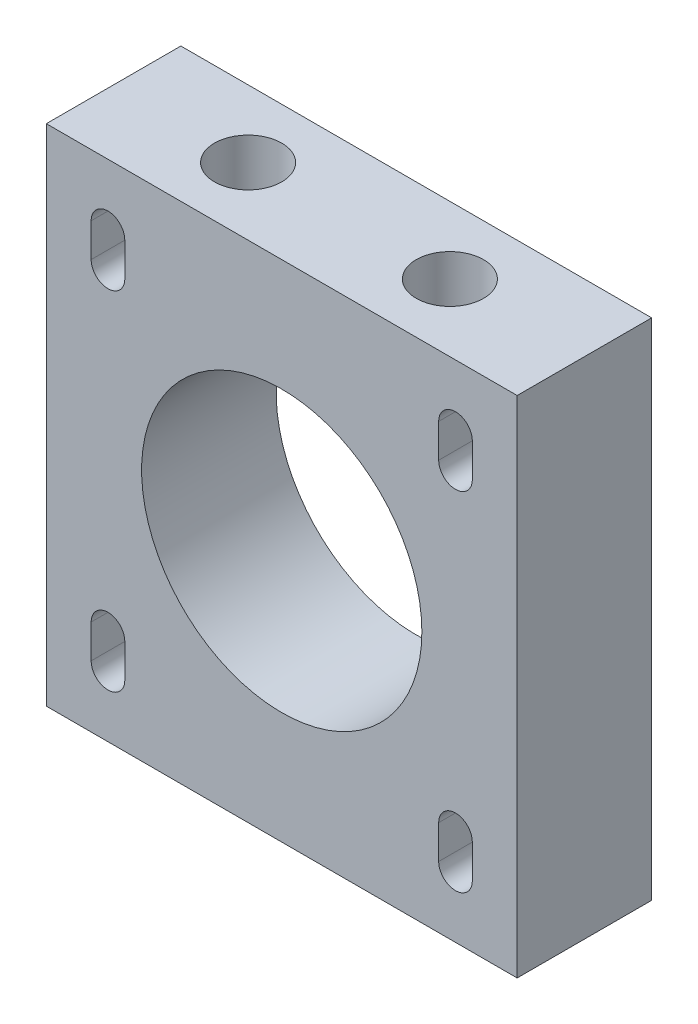
SolidWorks part; units mm, degrees
ref_plane "前视基准面" through (0, 0, 0) normal (0, 0, 1) x (1, 0, 0)
ref_plane "上视基准面" through (0, 0, 0) normal (0, 1, 0) x (1, 0, 0)
ref_plane "右视基准面" through (0, 0, 0) normal (1, 0, 0) x (0, 0, -1)
sketch "草图1" plane through (0, 0, 0) normal (0, 0, 1) x (1, 0, 0)
  line L0 (0, 12.6641) -> (0, 0) construction
  line L1 (21, -22.5) -> (-21, -22.5)
  line L2 (21, -22.5) -> (21, 22.5)
  line L3 (21, 22.5) -> (-21, 22.5)
  line L4 (-21, -22.5) -> (-21, 22.5)
  line L5 (21, -22.5) -> (-21, 22.5) construction
  line L6 (21, 22.5) -> (-21, -22.5) construction
  line L7 (0, 0) -> (9.215, 0) construction
  line L8 (-15.5, 17) -> (-15.5, 14) construction
  line L9 (-14, 17) -> (-14, 14)
  line L10 (-17, 17) -> (-17, 14)
  line L11 (15.5, 17) -> (15.5, 14) construction
  line L12 (14, 17) -> (14, 14)
  line L13 (17, 17) -> (17, 14)
  line L14 (15.5, -17) -> (15.5, -14) construction
  line L15 (14, -17) -> (14, -14)
  line L16 (17, -17) -> (17, -14)
  line L17 (-15.5, -17) -> (-15.5, -14) construction
  line L18 (-14, -17) -> (-14, -14)
  line L19 (-17, -17) -> (-17, -14)
  arc A1 (-14, 17) -> (-17, 17) centre (-15.5, 17) ccw
  arc A2 (-17, 14) -> (-14, 14) centre (-15.5, 14) ccw
  arc A3 (14, 17) -> (17, 17) centre (15.5, 17) cw
  arc A4 (17, 14) -> (14, 14) centre (15.5, 14) cw
  arc A5 (14, -17) -> (17, -17) centre (15.5, -17) ccw
  arc A6 (17, -14) -> (14, -14) centre (15.5, -14) ccw
  arc A7 (-14, -17) -> (-17, -17) centre (-15.5, -17) cw
  arc A8 (-17, -14) -> (-14, -14) centre (-15.5, -14) cw
  circle A9 centre (0, 0) radius 12.5
  point P0 (0, 0)
  point P10 (-15.5, 15.5)
  point P16 (-14, 15.5)
  point P19 (15.5, 15.5)
  point P26 (15.5, -15.5)
  point P33 (-15.5, -15.5)
  dimension "D3" = 3
  dimension "D4" = 3
  dimension "D7" = 25
  dimension "D1" = 42
  dimension "D2" = 45
  dimension "D5" = 31
  dimension "D6" = 31
extrude "凸台-拉伸1" add sketch "草图1" along normal blind 12
sketch "草图2" plane through (0, 22.5, 0) normal (0, 1, 0) x (1, 0, 0)
  line L0 (21, 0) -> (-21, 0) construction
  circle A0 centre (-9, -6) radius 3
  circle A1 centre (9, -6) radius 3
  point P6 (0, 0)
  dimension "D1" = 6
  dimension "D2" = 6
  dimension "D3" = 6
  dimension "D4" = 6
  dimension "D5" = 9
  dimension "D6" = 9
extrude "切除-拉伸2" cut sketch "草图2" against normal blind 10
